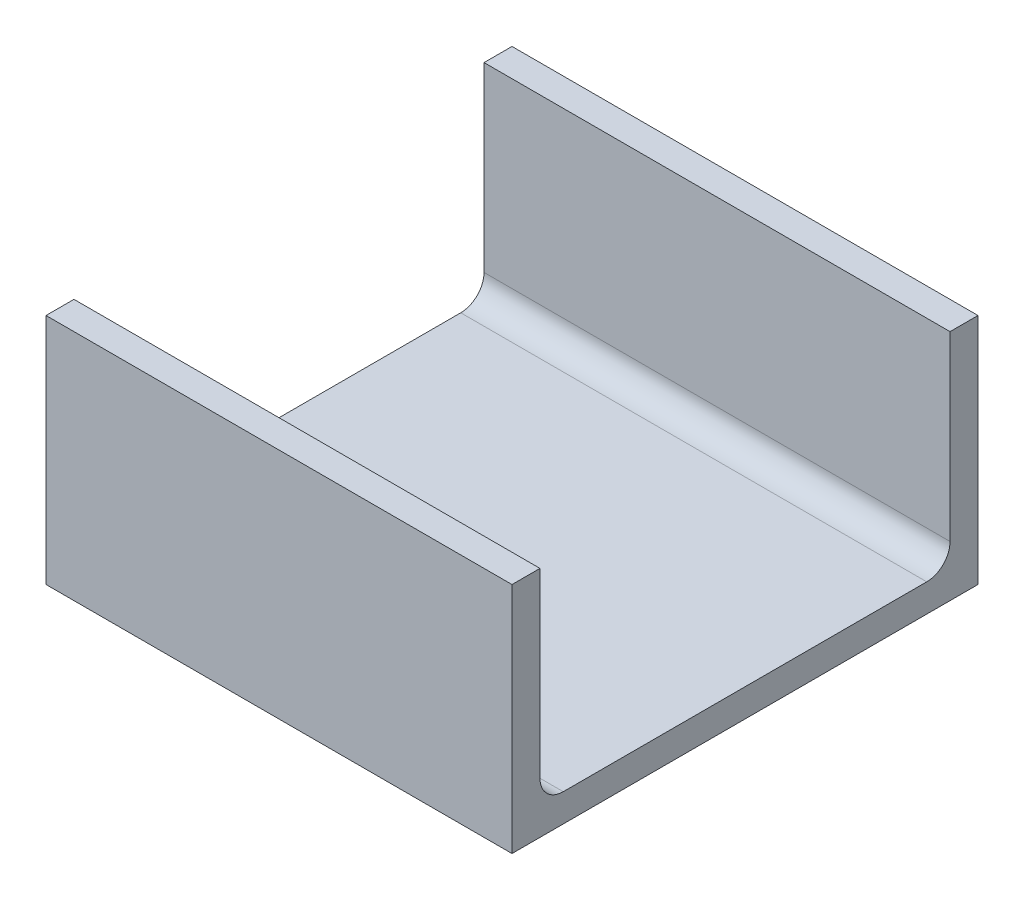
SolidWorks part; units mm, degrees
ref_plane "Front Plane" through (0, 0, 0) normal (0, 0, 1) x (1, 0, 0)
ref_plane "Top Plane" through (0, 0, 0) normal (0, 1, 0) x (1, 0, 0)
ref_plane "Right Plane" through (0, 0, 0) normal (1, 0, 0) x (0, 0, -1)
sketch "Sketch1" plane through (0, 0, 0) normal (1, 0, 0) x (0, 0, -1)
  line L0 (-22.352, 9.652) -> (22.352, 9.652)
  line L1 (-25.4, -12.7) -> (25.4, -12.7)
  line L2 (-25.4, -12.7) -> (-25.4, 12.7)
  line L3 (-25.4, 12.7) -> (25.4, 12.7)
  line L4 (25.4, -12.7) -> (25.4, 12.7)
  line L5 (-25.4, -12.7) -> (25.4, 12.7) construction
  line L6 (-25.4, 12.7) -> (25.4, -12.7) construction
  line L7 (22.352, -7.112) -> (22.352, 9.652)
  line L8 (-19.812, -9.652) -> (19.812, -9.652)
  line L9 (-22.352, -7.112) -> (-22.352, 9.652)
  line L10 (-22.352, 9.652) -> (-22.352, 12.7)
  line L11 (22.352, 9.652) -> (22.352, 12.7)
  line L12 (22.352, -9.652) -> (22.352, 9.652) construction
  line L13 (-22.352, -9.652) -> (22.352, -9.652) construction
  line L14 (-22.352, -9.652) -> (-22.352, 9.652) construction
  arc A0 (22.352, -7.112) -> (19.812, -9.652) centre (19.812, -7.112) cw
  arc A1 (-19.812, -9.652) -> (-22.352, -7.112) centre (-19.812, -7.112) cw
  point P0 (0, 0)
  dimension "D4" = 2.54
  dimension "D1" = 25.4
  dimension "D2" = 50.8
  dimension "D3" = 3.048
extrude "Boss-Extrude1" add sketch "Sketch1" along normal blind 50.8 contours L8 A1 L9 L10 L3 L2 L1 L4 L11 L7 A0
